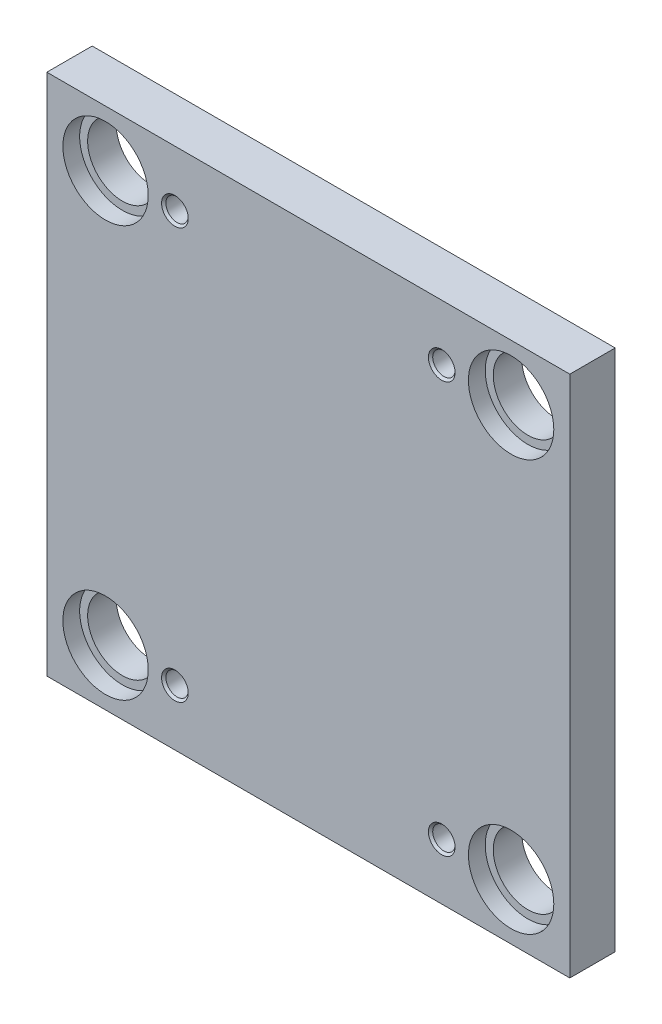
SolidWorks part; units mm, degrees
ref_plane "Спереди" through (0, 0, 0) normal (0, 0, 1) x (1, 0, 0)
ref_plane "Сверху" through (0, 0, 0) normal (0, 1, 0) x (1, 0, 0)
ref_plane "Справа" through (0, 0, 0) normal (1, 0, 0) x (0, 0, -1)
ref_plane "Плоскость4" through (0, 0, 17) normal (0, 0, 1) x (1, 0, 0)
sketch "Эскиз1" plane through (0, 0, 17) normal (0, 0, 1) x (1, 0, 0)
  line L0 (98, 98) -> (-98, 98)
  line L1 (-98, 98) -> (-98, -98)
  line L2 (-98, -98) -> (98, -98)
  line L3 (98, -98) -> (98, 98)
extrude "Бобышка-Вытянуть1" add sketch "Эскиз1" against normal blind 17
hole_wizard "Отверстие1" positions "Эскиз3" profile "Эскиз2" legacy
sketch "Эскиз3" plane through (0, 0, 17) normal (0, 0, 1) x (1, 0, 0)
  point P0 (-50, 77)
  point P1 (-50, -77)
  point P2 (50, 77)
  point P3 (50, -77)
sketch "Эскиз2" plane through (-50, 77, 17) normal (1, 0, 0) x (0, -1, 0)
  line L0 (0, 0) -> (0, 17)
  line L1 (0, 17) -> (4.188, 17)
  line L2 (4.188, 17) -> (4.188, 0)
  line L3 (4.188, 0) -> (0, 0)
  line L4 (0, 110) -> (0, -10) construction
  dimension "Диаметр" = 8.376
  dimension "Глубина" = 17
hole_wizard "Цековка для  болта с шестигранной головкой M241" positions "Эскиз5" profile "Эскиз4" counterbore size "M24" standard "Ansi Metric"
sketch "Эскиз5" plane through (0, 0, 17) normal (0, 0, 1) x (1, 0, 0)
  point P0 (76, -77)
  point P1 (-76, -77)
  point P2 (76, 77)
  point P3 (-76, 77)
sketch "Эскиз4" plane through (76, -77, 17) normal (1, 0, 0) x (0, -1, 0)
  line L0 (0, 0) -> (0, 17)
  line L1 (0, 17) -> (13, 17)
  line L3 (13, 17) -> (13, 6.3)
  line L4 (13, 6.3) -> (16, 6.3)
  line L5 (16, 6.3) -> (16, 0)
  line L7 (16, 0) -> (0, 0)
  line L11 (0, -6.35) -> (0, 107.95) construction
  dimension "Диаметр сквозного отверстия" = 26
  dimension "Глубина сквозного отверстия" = 17
  dimension "Диаметр цековки" = 32
  dimension "Глубина цековки" = 6.3
chamfer "Фаска1" distance 0.812 angle 45 4 edges at (54.188, -77, 17) (54.188, 77, 17) (-45.812, 77, 17) (-45.812, -77, 17)
